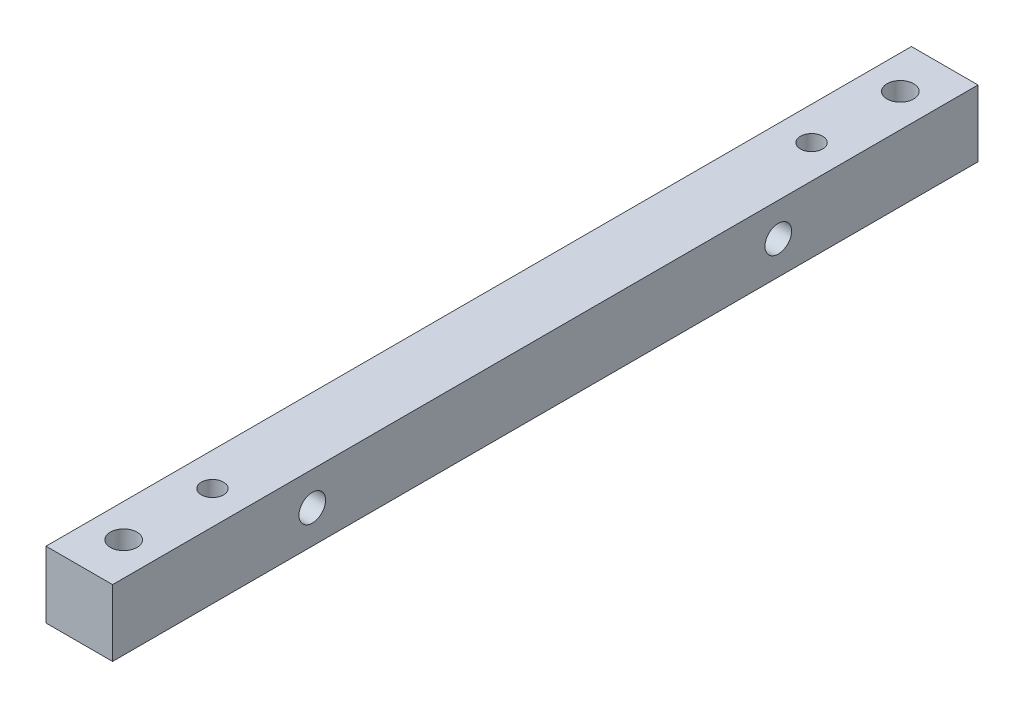
SolidWorks part; units mm, degrees
other "细节项目1"
other "细节项目2"
material "6061-T6 (SS)"
ref_plane "前视基准面" through (0, 0, 0) normal (0, 0, 1) x (1, 0, 0)
ref_plane "上视基准面" through (0, 0, 0) normal (0, 1, 0) x (1, 0, 0)
ref_plane "右视基准面" through (0, 0, 0) normal (1, 0, 0) x (0, 0, -1)
sketch "草图1" plane through (0, 0, 0) normal (0, 0, 1) x (1, 0, 0)
  line L1 (0, 0) -> (6, 0)
  line L2 (0, 0) -> (0, 6)
  line L3 (0, 6) -> (6, 6)
  line L4 (6, 0) -> (6, 6)
  dimension "D1" = 6
extrude "凸台-拉伸1" add sketch "草图1" along normal blind 78
sketch "草图2" plane through (0, 6, 0) normal (0, 1, 0) x (1, 0, 0)
  line L0 (3, -78) -> (3, -74) construction
  line L1 (6, -78) -> (0, -78) construction
  line L2 (3, -74) -> (3, -66) construction
  line L3 (3, -66) -> (3, -12) construction
  line L4 (3, -12) -> (3, -4) construction
  line L5 (3, -4) -> (3, 0) construction
  line L6 (6, 0) -> (0, 0) construction
  circle A0 centre (3, -74) radius 1.2
  circle A1 centre (3, -4) radius 1.2
  circle A2 centre (3, -12) radius 1
  circle A3 centre (3, -66) radius 1
  dimension "D3" = 2
  dimension "D4" = 2.4
  dimension "D1" = 54
  dimension "D2" = 8
extrude "切除-拉伸1" cut sketch "草图2" against normal blind 80
cosmetic thread "装饰螺纹线1" parameters "D2"=2.5
cosmetic thread "装饰螺纹线2" parameters "D2"=2.5
cosmetic thread "装饰螺纹线3" parameters "D2"=3
cosmetic thread "装饰螺纹线4" parameters "D2"=3
sketch "草图3" plane through (6, 0, 0) normal (1, 0, 0) x (0, 0, -1)
  line L0 (-78, 3) -> (-60, 3) construction
  line L1 (-78, 0) -> (-78, 6) construction
  line L2 (-60, 3) -> (-18, 3) construction
  line L3 (-18, 3) -> (0, 3) construction
  line L4 (0, 0) -> (0, 6) construction
  circle A0 centre (-60, 3) radius 1.2
  circle A1 centre (-18, 3) radius 1.2
  dimension "D2" = 2.4
  dimension "D1" = 42
extrude "切除-拉伸2" cut sketch "草图3" against normal blind 80
cosmetic thread "装饰螺纹线5"
cosmetic thread "装饰螺纹线6"
